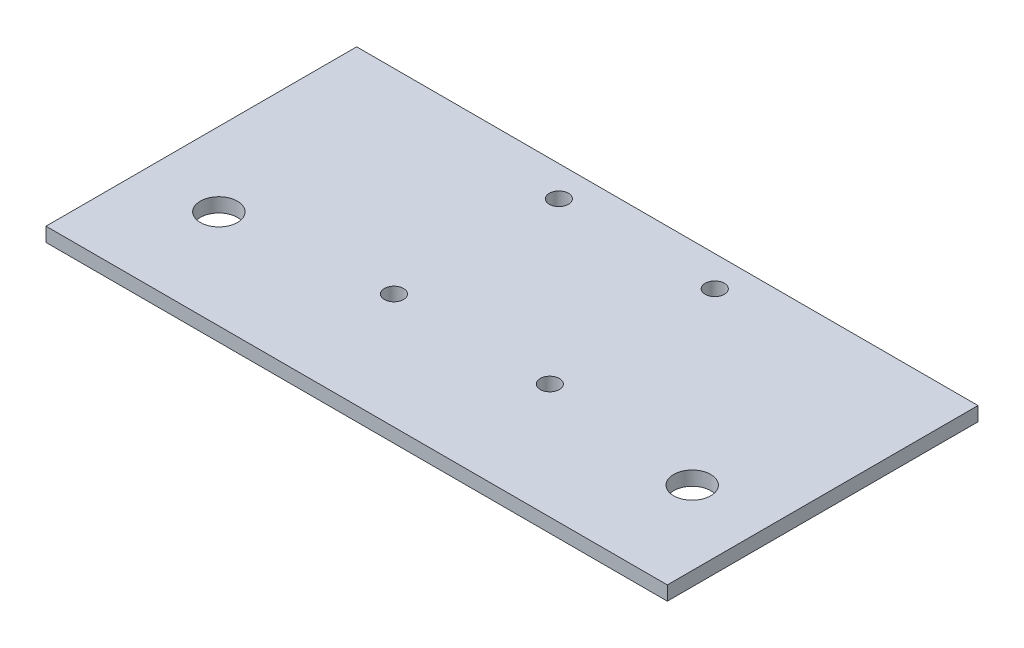
SolidWorks part; units mm, degrees
material "6061-T6 (SS)"
ref_plane "Front Plane" through (0, 0, 0) normal (0, 0, 1) x (1, 0, 0)
ref_plane "Top Plane" through (0, 0, 0) normal (0, 1, 0) x (1, 0, 0)
ref_plane "Right Plane" through (0, 0, 0) normal (1, 0, 0) x (0, 0, -1)
sketch "Sketch1" plane through (0, 0, 0) normal (0, 1, 0) x (1, 0, 0)
  line L0 (0, 0) -> (35.052, 0) construction
  line L1 (35.052, 0) -> (35.052, -37.084) construction
  line L2 (35.052, -37.084) -> (0, -37.084) construction
  line L3 (0, -37.084) -> (0, 0) construction
  line L5 (-52.324, 6.858) -> (87.376, 6.858)
  line L6 (-52.324, 6.858) -> (-52.324, -62.992)
  line L7 (-52.324, -62.992) -> (87.376, -62.992)
  line L8 (87.376, 6.858) -> (87.376, -62.992)
  circle A0 centre (0, 0) radius 2.159
  circle A1 centre (35.052, 0) radius 2.159
  circle A2 centre (0, -37.084) radius 2.159
  circle A3 centre (35.052, -37.084) radius 2.159
  circle A4 centre (-35.687, -40.767) radius 4.1656
  circle A5 centre (70.739, -40.767) radius 4.1656
  dimension "D1" = 4.318
  dimension "D2" = 4.318
  dimension "D3" = 4.318
  dimension "D4" = 4.318
  dimension "D11" = 8.3312
  dimension "D12" = 8.3312
  dimension "D5" = 35.052
  dimension "D6" = 139.7
  dimension "D7" = 37.084
  dimension "D8" = 52.324
  dimension "D9" = 6.858
  dimension "D10" = 69.85
  dimension "D13" = 16.637
  dimension "D14" = 16.637
  dimension "D15" = 22.225
  dimension "D16" = 22.225
extrude "Boss-Extrude1" add sketch "Sketch1" along normal blind 3.175
